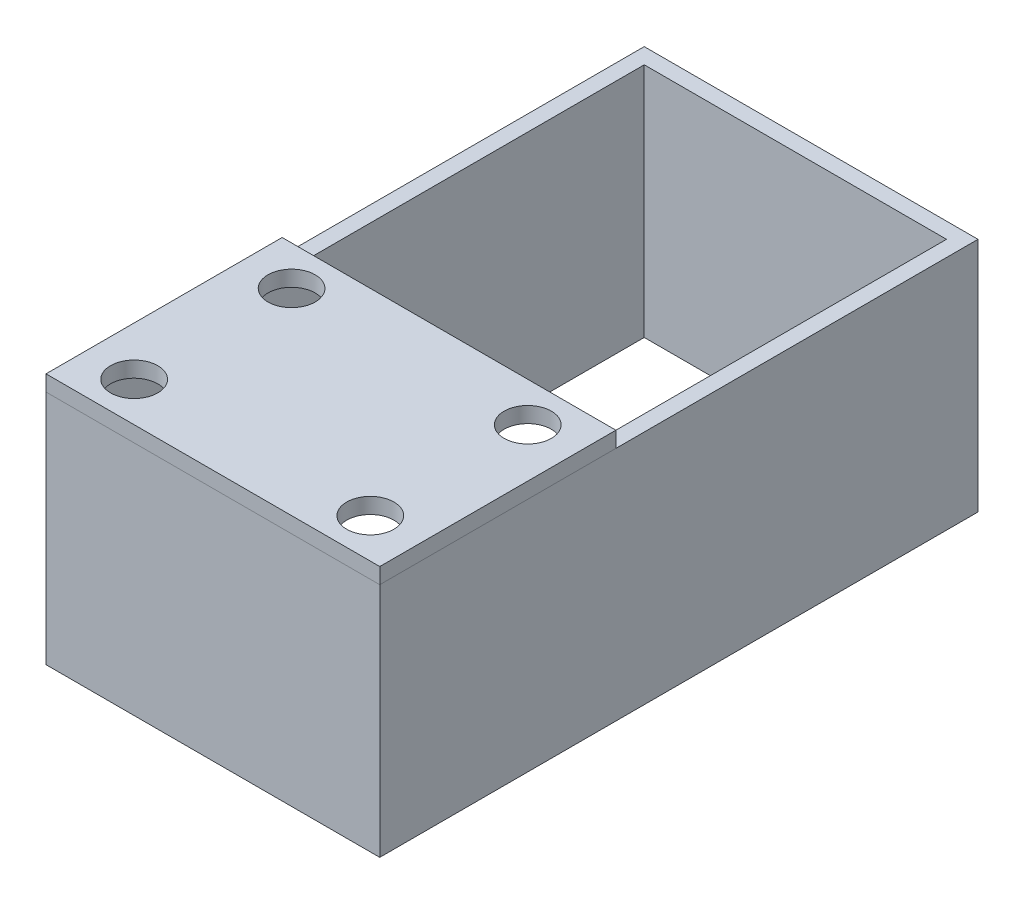
SolidWorks part; units mm, degrees
ref_plane "Front Plane" through (0, 0, 0) normal (0, 0, 1) x (1, 0, 0)
ref_plane "Top Plane" through (0, 0, 0) normal (0, 1, 0) x (1, 0, 0)
ref_plane "Right Plane" through (0, 0, 0) normal (1, 0, 0) x (0, 0, -1)
sketch "Sketch2" plane through (0, 0, 0) normal (0, 1, 0) x (1, 0, 0)
  line L0 (-2, -2) -> (-2, 74)
  line L1 (0, 0) -> (38.4, 0)
  line L2 (0, 0) -> (0, 72)
  line L3 (0, 72) -> (38.4, 72)
  line L4 (38.4, 0) -> (38.4, 72)
  line L5 (-2, 74) -> (40.4, 74)
  line L6 (40.4, -2) -> (40.4, 74)
  line L7 (-2, -2) -> (40.4, -2)
  dimension "D1" = 72
  dimension "D2" = 38.4
  dimension "D3" = 2
extrude "Boss-Extrude4" add sketch "Sketch2" along normal blind 30
sketch "Sketch1" plane through (0, 30, 0) normal (0, 1, 0) x (1, 0, 0)
  line L0 (19.2, 28) -> (19.2, -2) construction
  line L1 (-2, -2) -> (40.4, -2)
  line L2 (-2, -2) -> (-2, 28)
  line L3 (-2, 28) -> (40.4, 28)
  line L4 (40.4, -2) -> (40.4, 28)
  line L5 (-2, 13) -> (40.4, 13) construction
  line L6 (-2, -2) -> (40.4, -2) construction
  line L8 (40.4, -2) -> (40.4, 74) construction
  line L9 (-2, 74) -> (-2, -2) construction
  circle A0 centre (4.2, 3) radius 3
  circle A1 centre (34.2, 3) radius 3
  circle A2 centre (34.2, 23) radius 3
  circle A3 centre (4.2, 23) radius 3
  point P17 (0, 0)
  dimension "D3" = 6
  dimension "D1" = 30
  dimension "D2" = 20
  dimension "D4" = 30
extrude "Boss-Extrude1" add sketch "Sketch1" along normal blind 2
sketch "Sketch4" plane through (0, 30, 0) normal (0, 1, 0) x (1, 0, 0)
  line L1 (40.4, 28) -> (-2, 28)
  line L2 (40.4, 28) -> (40.4, 74)
  line L3 (40.4, 74) -> (-2, 74)
  line L4 (-2, 28) -> (-2, 74)
